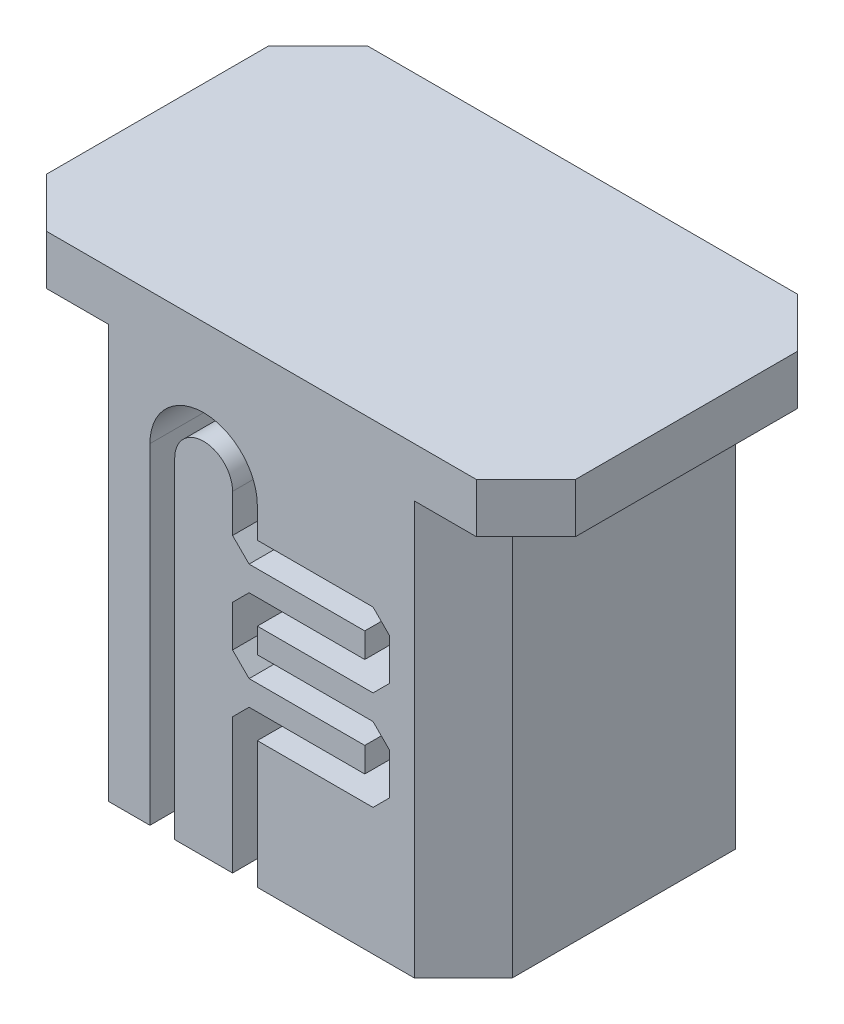
SolidWorks part; units mm, degrees
ref_plane "Front Plane" through (0, 0, 0) normal (0, 0, 1) x (1, 0, 0)
ref_plane "Top Plane" through (0, 0, 0) normal (0, 1, 0) x (1, 0, 0)
ref_plane "Right Plane" through (0, 0, 0) normal (1, 0, 0) x (0, 0, -1)
sketch "Sketch2" plane through (0, 0, 0) normal (0, 1, 0) x (1, 0, 0)
  line L0 (0, 0) -> (0, 13.5)
  line L1 (0, 13.5) -> (2.9628, 16.4628)
  line L2 (2.9628, 16.4628) -> (21.4628, 16.4628)
  line L3 (21.4628, 16.4628) -> (24.4256, 13.5)
  line L4 (24.4256, 13.5) -> (24.4256, 0)
  line L5 (24.4256, 0) -> (21.4628, -2.9628)
  line L6 (21.4628, -2.9628) -> (2.9628, -2.9628)
  line L7 (2.9628, -2.9628) -> (0, 0)
  dimension "D1" = 18.5
  dimension "D2" = 13.5
  dimension "D3" = 4.19
extrude "Boss-Extrude1" add sketch "Sketch2" along normal blind 25
sketch "Sketch3" plane through (0, 0, 2.9628) normal (0, 0, 1) x (1, 0, 0)
  line L0 (12.2128, 0) -> (12.2128, 25) construction
  line L1 (2.9628, 0) -> (21.4628, 0) construction
  line L2 (2.9628, 25) -> (21.4628, 25) construction
  line L3 (6.2128, 0) -> (6.2128, 20)
  line L4 (11.2128, 20) -> (11.2128, 17.4389)
  line L5 (11.2128, 17.4389) -> (19.2128, 17.4389)
  line L6 (19.2128, 17.4389) -> (19.2128, 14.4389)
  line L7 (19.2128, 14.4389) -> (11.2128, 14.4389)
  line L8 (11.2128, 14.4389) -> (11.2128, 11.4389)
  line L9 (11.2128, 11.4389) -> (19.2128, 11.4389)
  line L10 (19.2128, 11.4389) -> (19.2128, 8.4389)
  line L11 (19.2128, 8.4389) -> (11.2128, 8.4389)
  line L12 (11.2128, 8.4389) -> (11.2128, 0)
  arc A0 (6.2128, 20) -> (11.2128, 20) centre (8.7128, 20) cw
  dimension "D2" = 2.5
  dimension "D1" = 6
  dimension "D3" = 20
  dimension "D4" = 8
  dimension "D5" = 3
extrude "Cut-Extrude-Thin1" cut sketch "Sketch3" against normal blind 8.5 and the other way through all thin thin type mid plane wall 1.5
sketch "Sketch4" plane through (0, 0, -16.4628) normal (0, 0, -1) x (-1, 0, 0)
  line L0 (-12.2128, 25) -> (-12.2128, 0) construction
  line L1 (-21.4628, 25) -> (-2.9628, 25) construction
  line L2 (-21.4628, 0) -> (-2.9628, 0) construction
  line L3 (-18.2128, 0) -> (-18.2128, 19.7899)
  line L4 (-13.2128, 19.7899) -> (-13.2128, 16.7899)
  line L5 (-13.2128, 16.7899) -> (-5.2128, 16.7899)
  line L6 (-5.2128, 16.7899) -> (-5.2128, 13.7899)
  line L7 (-5.2128, 13.7899) -> (-13.2128, 13.7899)
  line L8 (-13.2128, 13.7899) -> (-13.2128, 10.7899)
  line L9 (-13.2128, 10.7899) -> (-5.2128, 10.7899)
  line L10 (-5.2128, 10.7899) -> (-5.2128, 7.7899)
  line L11 (-5.2128, 7.7899) -> (-13.2128, 7.7899)
  line L12 (-13.2128, 7.7899) -> (-13.2128, 0)
  arc A0 (-18.2128, 19.7899) -> (-13.2128, 19.7899) centre (-15.7128, 19.7899) cw
  dimension "D2" = 2.5
  dimension "D1" = 6
  dimension "D3" = 8
  dimension "D4" = 3
extrude "Cut-Extrude-Thin3" cut sketch "Sketch4" against normal blind 8.5 and the other way through all thin thin type mid plane wall 1.5
sketch "Sketch5" plane through (0, 25, 0) normal (0, 1, 0) x (1, 0, 0)
  line L0 (12.2128, 16.4628) -> (12.2128, -2.9628) construction
  line L1 (21.4628, 16.4628) -> (2.9628, 16.4628) construction
  line L2 (2.9628, -2.9628) -> (21.4628, -2.9628) construction
  line L4 (-3.7872, -2.9628) -> (28.2128, -2.9628)
  line L5 (-3.7872, -2.9628) -> (-3.7872, 16.4628)
  line L6 (-3.7872, 16.4628) -> (28.2128, 16.4628)
  line L7 (28.2128, -2.9628) -> (28.2128, 16.4628)
  line L8 (-3.7872, -2.9628) -> (28.2128, 16.4628) construction
  line L9 (-3.7872, 16.4628) -> (28.2128, -2.9628) construction
  point P6 (12.2128, 6.75)
  dimension "D1" = 32
extrude "Boss-Extrude2" add sketch "Sketch5" along normal blind 3
chamfer "Chamfer3" distance 3 angle 45 4 edges at (28.2128, 26.5, 2.9628) (28.2128, 26.5, -16.4628) (-3.7872, 26.5, 2.9628) (-3.7872, 26.5, -16.4628)
chamfer "Chamfer4" distance 1 angle 45 16 edges at (4.4628, 17.5399, -12.2128) (4.4628, 11.5399, -12.2128) (4.4628, 7.0399, -12.2128) (4.4628, 13.0399, -12.2128) (19.9628, 12.1889, -1.2872) (19.9628, 7.6889, -1.2872) (19.9628, 13.6889, -1.2872) (19.9628, 18.1889, -1.2872) (10.4628, 9.1889, -1.2872) (10.4628, 15.1889, -1.2872) (10.4628, 10.6889, -1.2872) (10.4628, 16.6889, -1.2872) (13.9628, 8.5399, -12.2128) (13.9628, 10.0399, -12.2128) (13.9628, 14.5399, -12.2128) (13.9628, 16.0399, -12.2128)
